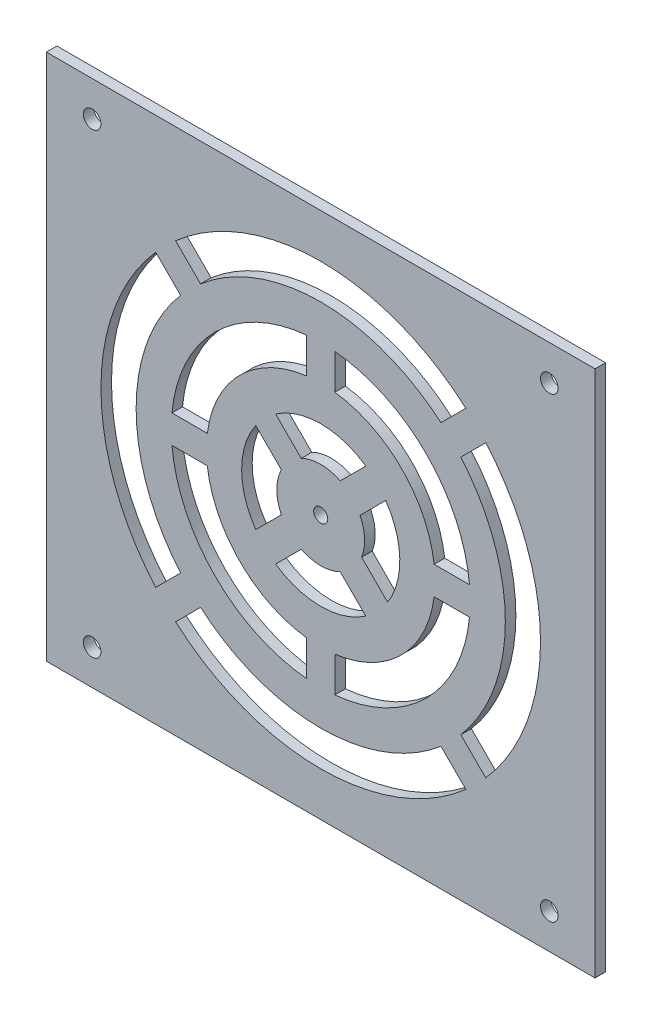
SolidWorks part; units mm, degrees
ref_plane "Front Plane" through (0, 0, 0) normal (0, 0, 1) x (1, 0, 0)
ref_plane "Top Plane" through (0, 0, 0) normal (0, 1, 0) x (1, 0, 0)
ref_plane "Right Plane" through (0, 0, 0) normal (1, 0, 0) x (0, 0, -1)
sketch "Sketch1" plane through (0, 0, 0) normal (0, 0, 1) x (1, 0, 0)
  line L1 (71.8966, -8.7931) -> (221.8966, -8.7931)
  line L2 (71.8966, -8.7931) -> (71.8966, 141.2069)
  line L3 (71.8966, 141.2069) -> (221.8966, 141.2069)
  line L4 (221.8966, -8.7931) -> (221.8966, 141.2069)
  line L5 (71.8966, -8.7931) -> (221.8966, 141.2069) construction
  line L6 (71.8966, 141.2069) -> (221.8966, -8.7931) construction
  dimension "D1" = 150
  dimension "D2" = 150
extrude "Boss-Extrude1" add sketch "Sketch1" along normal blind 3
sketch "Sketch2" plane through (0, 0, 3) normal (0, 0, 1) x (1, 0, 0)
  line L0 (99.9731, 107.4735) -> (107.0615, 100.3851)
  line L1 (146.8966, 141.2069) -> (146.8966, 128.6948) construction
  line L2 (221.8966, 141.2069) -> (71.8966, 141.2069) construction
  line L3 (146.8966, -8.7931) -> (146.8966, 3.719) construction
  line L4 (71.8966, -8.7931) -> (221.8966, -8.7931) construction
  line L5 (71.8966, 141.2069) -> (221.8966, -8.7931) construction
  line L6 (71.8966, -8.7931) -> (221.8966, 141.2069) construction
  line L7 (105.63, 113.1303) -> (112.7184, 106.0419)
  line L8 (109.1742, 109.5861) -> (106.3457, 106.7577) construction
  line L9 (106.3457, 106.7577) -> (103.5173, 103.9293) construction
  line L10 (187.4474, 25.6561) -> (184.6189, 22.8277) construction
  line L11 (190.2758, 28.4845) -> (187.4474, 25.6561) construction
  line L12 (193.82, 24.9403) -> (186.7316, 32.0287)
  line L13 (188.1631, 19.2835) -> (181.0747, 26.3719)
  line L14 (186.7316, 100.3851) -> (193.82, 107.4735)
  line L15 (181.0747, 106.0419) -> (188.1631, 113.1303)
  line L16 (184.6189, 109.5861) -> (187.4474, 106.7577) construction
  line L17 (187.4474, 106.7577) -> (190.2758, 103.9293) construction
  line L18 (106.3457, 25.6561) -> (109.1742, 22.8277) construction
  line L19 (103.5173, 28.4845) -> (106.3457, 25.6561) construction
  line L20 (112.7184, 26.3719) -> (105.63, 19.2835)
  line L21 (107.0615, 32.0287) -> (99.9731, 24.9403)
  line L22 (146.8966, 141.2069) -> (146.8966, -8.7931) construction
  line L23 (221.8966, 66.2069) -> (71.8966, 66.2069) construction
  line L24 (221.8966, -8.7931) -> (221.8966, 141.2069) construction
  line L25 (71.8966, 141.2069) -> (71.8966, -8.7931) construction
  line L26 (150.8966, 108.5061) -> (150.8966, 98.4476)
  line L27 (142.8966, 108.5061) -> (142.8966, 98.4476)
  line L28 (142.8966, 103.4769) -> (146.8966, 103.4769) construction
  line L29 (146.8966, 103.4769) -> (150.8966, 103.4769) construction
  line L30 (142.8966, 28.9369) -> (146.8966, 28.9369) construction
  line L31 (146.8966, 28.9369) -> (150.8966, 28.9369) construction
  line L32 (150.8966, 23.9077) -> (150.8966, 33.9662)
  line L33 (142.8966, 23.9077) -> (142.8966, 33.9662)
  line L34 (189.1957, 70.2069) -> (179.1373, 70.2069)
  line L35 (189.1957, 62.2069) -> (179.1373, 62.2069)
  line L36 (184.1665, 70.2069) -> (184.1665, 66.2069) construction
  line L37 (184.1665, 66.2069) -> (184.1665, 62.2069) construction
  line L38 (109.6266, 70.2069) -> (109.6266, 66.2069) construction
  line L39 (109.6266, 66.2069) -> (109.6266, 62.2069) construction
  line L40 (104.5974, 62.2069) -> (114.6558, 62.2069)
  line L41 (104.5974, 70.2069) -> (114.6558, 70.2069)
  line L42 (181.0747, 106.0419) -> (107.0615, 32.0287) construction
  line L43 (112.7184, 26.3719) -> (186.7316, 100.3851) construction
  line L44 (135.7031, 71.7435) -> (128.4204, 79.0262)
  line L45 (107.0615, 100.3851) -> (181.0747, 26.3719) construction
  line L46 (152.4332, 77.4004) -> (159.7159, 84.6831)
  line L47 (165.3728, 79.0262) -> (158.09, 71.7435)
  line L48 (141.3599, 55.0134) -> (134.0772, 47.7307)
  line L49 (135.7031, 60.6703) -> (128.4204, 53.3875)
  line L50 (158.5217, 61.6459) -> (165.9328, 54.2349)
  line L51 (159.7159, 47.7307) -> (152.4332, 55.0134)
  line L52 (134.0772, 84.6831) -> (141.3599, 77.4004)
  circle A1 centre (146.8966, 66.2069) radius 62.4879
  circle A2 centre (146.8966, 66.2069) radius 52.4879
  circle A3 centre (146.8966, 66.2069) radius 42.4879
  circle A4 centre (146.8966, 66.2069) radius 32.4879
  circle A5 centre (146.8966, 66.2069) radius 22.4879
  circle A6 centre (146.8966, 66.2069) radius 12.4879
  dimension "D1" = 10
  dimension "D3" = 10
  dimension "D7" = 10
  dimension "D9" = 10
  dimension "D10" = 10
  dimension "D4" = 8
  dimension "D5" = 8
  dimension "D6" = 8
  dimension "D8" = 8
  dimension "D11" = 8
extrude "Cut-Extrude1" cut sketch "Sketch2" against normal through all contours A2 L15 A1 L7 | A2 L0 A1 L21 | A2 L12 A1 L14 | A2 L20 A1 L13 | A4 L32 A3 L35 | A4 L40 A3 L33 | A4 L27 A3 L41 | A4 L34 A3 L26 | A6 L50 A5 L47 | A6 L46 A5 L52 | A6 L44 A5 L49 | A6 L48 A5 L51
sketch "Sketch4" plane through (0, 0, 3) normal (0, 0, 1) x (1, 0, 0)
  line L0 (81.8966, 141.2069) -> (81.8966, 131.2069) construction
  line L1 (221.8966, 141.2069) -> (71.8966, 141.2069) construction
  line L2 (81.8966, 131.2069) -> (71.8966, 131.2069) construction
  line L3 (71.8966, 141.2069) -> (71.8966, -8.7931) construction
  circle A1 centre (81.8966, 131.2069) radius 2.5
  circle A2 centre (211.8966, 131.2069) radius 2.5
  circle A3 centre (211.8966, 1.2069) radius 2.5
  circle A4 centre (81.8966, 1.2069) radius 2.5
  point P17 (146.8966, 66.2069)
  dimension "D2" = 5
  dimension "D1" = 10
  dimension "D3" = 4
extrude "Cut-Extrude2" cut sketch "Sketch4" against normal blind 3
sketch "Sketch5" plane through (0, 0, 0) normal (0, 0, -1) x (-1, 0, 0)
  line L0 (-224.8966, 141.2069) -> (-221.8966, 141.2069)
  line L2 (-224.8966, 141.2069) -> (-224.8966, -8.7931)
  line L4 (-221.8966, 141.2069) -> (-221.8966, -8.7931)
  line L5 (-221.8966, -8.7931) -> (-71.8966, -8.7931)
  line L6 (-71.8966, -8.7931) -> (-71.8966, 141.2069)
  line L7 (-71.8966, 141.2069) -> (-221.8966, 141.2069)
  line L8 (-221.8966, 141.2069) -> (-221.8966, -8.7931)
  line L10 (-71.8966, -8.7931) -> (-71.8966, 141.2069)
  line L12 (-68.8966, 141.2069) -> (-68.8966, -8.7931)
  line L13 (-224.8966, 141.2069) -> (-68.8966, -8.7931) construction
  line L14 (-224.8966, -8.7931) -> (-68.8966, 141.2069) construction
  line L15 (-71.8966, 141.2069) -> (-68.8966, 141.2069)
  line L16 (-68.8966, -8.7931) -> (-71.8966, -8.7931)
  line L17 (-224.8966, -8.7931) -> (-221.8966, -8.7931)
  point P2 (-146.8966, 66.2069)
  dimension "D2" = 3
  dimension "D1" = 0
extrude "Boss-Extrude2" add sketch "Sketch5" against normal blind 3
sketch "Sketch6" plane through (0, 0, 3) normal (0, 0, 1) x (1, 0, 0)
  circle A0 centre (146.8966, 66.2069) radius 2
extrude "Cut-Extrude3" cut sketch "Sketch6" against normal blind 10
